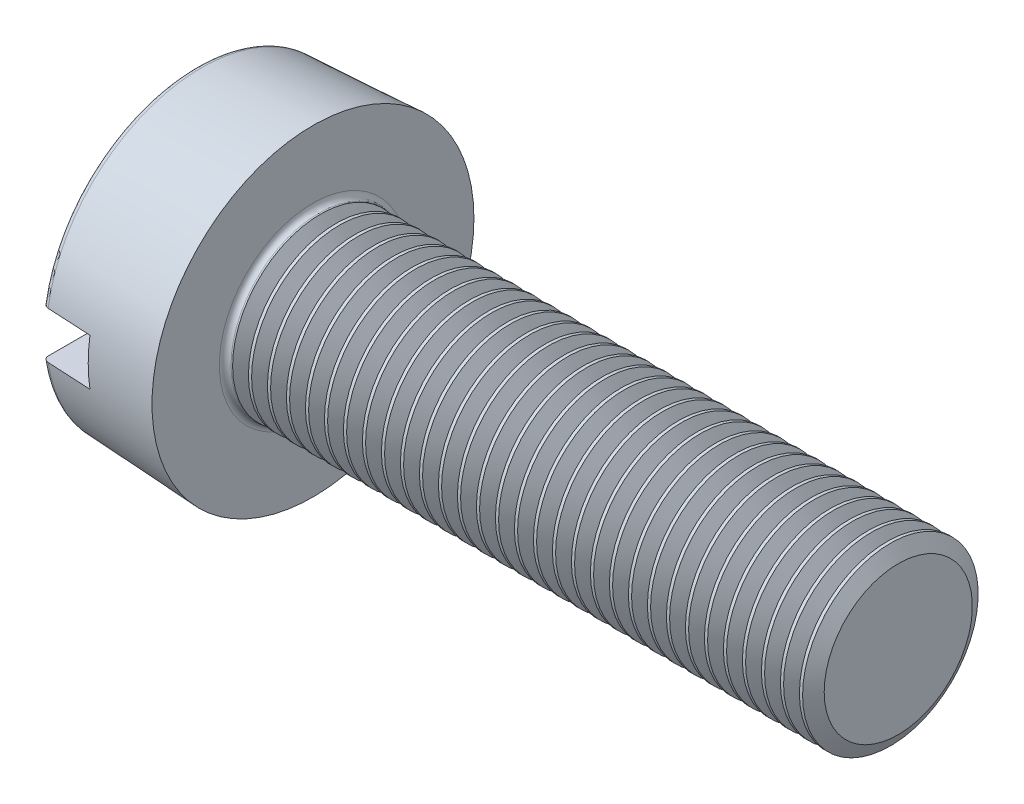
SolidWorks part; units mm, degrees
ref_plane "Front" through (0, 0, 0) normal (0, 0, 1) x (1, 0, 0)
ref_plane "Top" through (0, 0, 0) normal (0, 1, 0) x (1, 0, 0)
ref_plane "Right" through (0, 0, 0) normal (1, 0, 0) x (0, 0, -1)
ref_plane "Plane1" through (2, 0, 0) normal (1, 0, 0) x (0, 0, -1)
sketch "Sketch2" plane through (2, 0, 0) normal (1, 0, 0) x (0, 0, -1)
  circle A0 centre (0, 0) radius 2.75
  dimension "dk" = 5.5
extrude "BaseHead" add sketch "Sketch2" against normal blind 2 draft 3
sketch "Sketch3" plane through (2, -1.1101, -1.3544) normal (1, 0, 0) x (0, 0, -1)
  line L0 (-1.3544, 1.1101) -> (-0.3544, 1.1101) construction
  circle A0 centre (-1.3544, 1.1101) radius 1.5
  circle A1 centre (-1.3544, 1.1101) radius 2.75 construction
  dimension "d" = 3
  dimension "a" = 1
extrude "BaseBody" add sketch "Sketch3" along normal blind 10
cosmetic thread "ThreadCosmetic1" [suppressed] parameters "D1"=10, "D2"=2.459
sketch "Sketch4" plane through (-1.9, -1.9, 0) normal (0, 0, 1) x (0, 1, 0)
  line L1 (1.5, -1.9) -> (2.3, -1.9)
  line L2 (1.5, -1.9) -> (1.5, -2.75)
  line L3 (1.5, -2.75) -> (2.3, -2.75)
  line L4 (2.3, -1.9) -> (2.3, -2.75)
  line L5 (4.5452, -1.9) -> (-0.7452, -1.9) construction
  dimension "n" = 0.8
  dimension "t" = 0.85
  dimension "m" = 0.4
extrude "Slot" cut sketch "Sketch4" against normal through all and the other way through all
fillet "HeadFillet" radius 0.1 3 edges at (2, 0, -1.5) (0, -2.6452, 0) (0, 2.6452, 0)
sketch "Sketch1" plane through (0, 0, 0) normal (0, 0, 1) x (1, 0, 0)
  line L0 (5.5483, 0) -> (-2.9147, 0) construction
  line L1 (2, 6.2295) -> (-13, 6.2295)
  line L2 (2, 6.2295) -> (2, 1.2295)
  line L3 (2, 1.2295) -> (-14.25, 1.2295)
  line L8 (-13, 1.5) -> (-14.25, 1.2295)
  line L9 (-13, 6.2295) -> (-13, 1.5)
  line L10 (2, -2.75) -> (2, 2.75) construction
  line L11 (12, -1.5) -> (12, 1.5) construction
  line L12 (12, 1.5) -> (2.1, 1.5) construction
  dimension "b1" = 2.459
  dimension "b" = 25
  dimension "x" = 1.25
  dimension "dd" = 5
sketch "Sketch5" plane through (0, 0, 0) normal (0, 0, 1) x (1, 0, 0)
  line L0 (12.1352, 1.5) -> (12.1352, 1.7705)
  line L1 (12.1352, 1.7705) -> (11.8647, 1.7705)
  line L2 (11.8647, 1.7705) -> (11.8647, 1.5)
  line L3 (11.8647, 1.5) -> (12, 1.2657)
  line L4 (12, 1.2657) -> (12.1352, 1.5)
  line L5 (12, -1.5) -> (12, 1.5) construction
  line L6 (0, 0) -> (15.9087, 0) construction
  dimension "D1" = 3
  dimension "D2" = 0.2705
revolve "Cut-Revolve10" cut sketch "Sketch5" angle 360 about L6
pattern_linear "LPattern10" count 31 spacing 0.3246 along (-1, 0, 0) of "Cut-Revolve10"
equation "\"m@Sketch4\" = \"n@Sketch4\" / 2"
equation "\"D1@Plane1\"=\"k@BaseHead\""
equation "\"D1@Sketch5\" = \"d@Sketch3\""
equation "\"D2@Sketch5\" =  ( \"d@Sketch3\" - \"D2@ThreadCosmetic1\" )  / 2"
equation "\"D3@LPattern10\" = \"D2@Sketch5\" * 1.2"
equation "\"D1@LPattern10\" = \"D1@ThreadCosmetic1\" / \"D3@LPattern10\""
